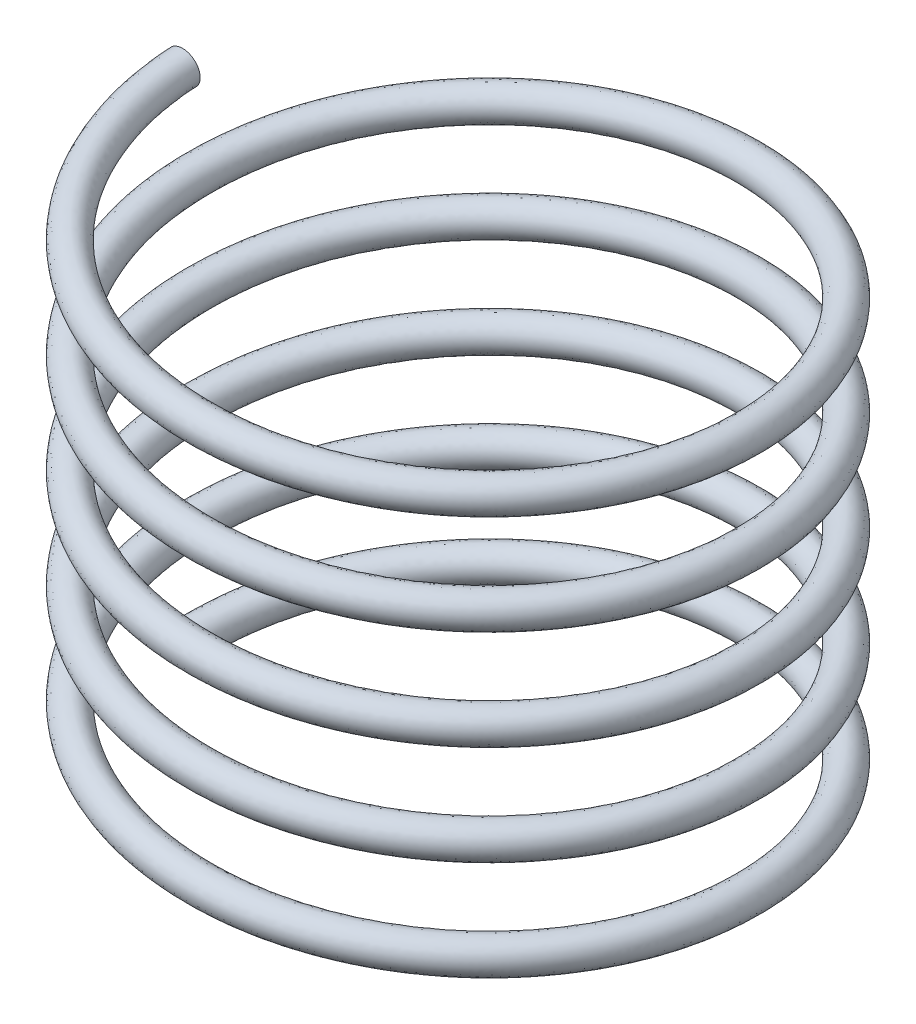
SolidWorks part; units mm, degrees
ref_plane "Front Plane" through (0, 0, 0) normal (0, 0, 1) x (1, 0, 0)
ref_plane "Top Plane" through (0, 0, 0) normal (0, 1, 0) x (1, 0, 0)
ref_plane "Right Plane" through (0, 0, 0) normal (1, 0, 0) x (0, 0, -1)
sketch "Sketch1" plane through (0, 0, 0) normal (0, 1, 0) x (1, 0, 0)
  circle A0 centre (0, 0) radius 6.6
  dimension "D1" = 13.2
curve "Helix/Spiral1" pitch 2.4 height 12 turns 5
sweep "Sweep1" add path "Helix/Spiral1" circular profile diameter 0.8 parameters "D3"=0.8
